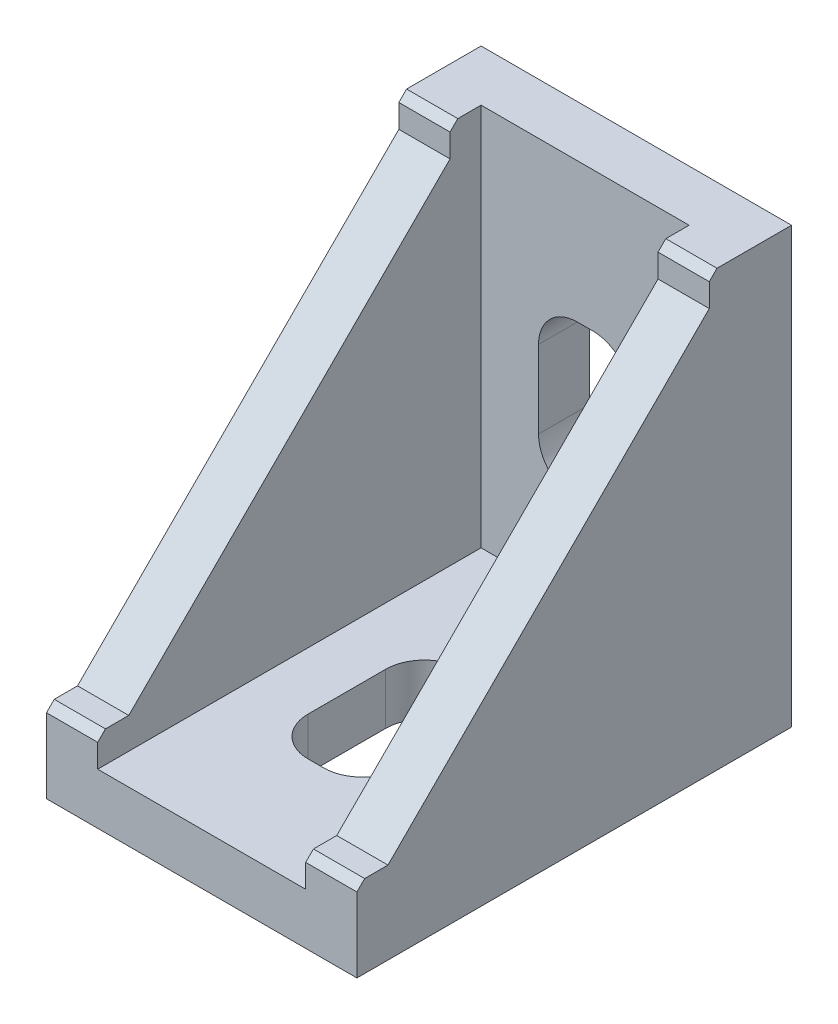
SolidWorks part; units mm, degrees
ref_plane "Front Plane" through (0, 0, 0) normal (0, 0, 1) x (1, 0, 0)
ref_plane "Top Plane" through (0, 0, 0) normal (0, 1, 0) x (1, 0, 0)
ref_plane "Right Plane" through (0, 0, 0) normal (1, 0, 0) x (0, 0, -1)
sketch "Sketch1" plane through (0, 0, 0) normal (0, 0, 1) x (1, 0, 0)
  line L0 (10, 28) -> (10, 0) construction
  line L1 (0, 0) -> (20, 0)
  line L2 (0, 0) -> (0, 28)
  line L3 (0, 28) -> (20, 28)
  line L4 (20, 0) -> (20, 28)
  line L5 (0, 14) -> (20, 14) construction
  line L7 (10.5, 9) -> (9.5, 9)
  line L8 (13, 11.5) -> (13, 16.5)
  line L9 (10.5, 19) -> (9.5, 19)
  line L10 (7, 11.5) -> (7, 16.5)
  line L11 (13, 9) -> (7, 19) construction
  line L12 (13, 19) -> (7, 9) construction
  arc A0 (10.5, 9) -> (13, 11.5) centre (10.5, 11.5) ccw
  arc A1 (13, 16.5) -> (10.5, 19) centre (10.5, 16.5) ccw
  arc A2 (9.5, 9) -> (7, 11.5) centre (9.5, 11.5) cw
  arc A3 (9.5, 19) -> (7, 16.5) centre (9.5, 16.5) ccw
  point P9 (10, 14)
  dimension "D5" = 2.5
  dimension "D1" = 20
  dimension "D2" = 28
  dimension "D3" = 6
  dimension "D4" = 10
extrude "Boss-Extrude1" add sketch "Sketch1" against normal blind 3.3
sketch "Sketch2" plane through (0, 0, 0) normal (0, 1, 0) x (1, 0, 0)
  line L0 (10, -24.7) -> (10, 0) construction
  line L1 (0, 0) -> (20, 0)
  line L2 (0, 0) -> (0, -24.7)
  line L3 (0, -24.7) -> (20, -24.7)
  line L4 (20, 0) -> (20, -24.7)
  line L5 (10, -12.35) -> (0, -12.35) construction
  line L7 (10.5, -17.35) -> (9.5, -17.35)
  line L8 (13, -14.85) -> (13, -9.85)
  line L9 (10.5, -7.35) -> (9.5, -7.35)
  line L10 (7, -14.85) -> (7, -9.85)
  line L11 (13, -17.35) -> (7, -7.35) construction
  line L12 (13, -7.35) -> (7, -17.35) construction
  arc A0 (10.5, -17.35) -> (13, -14.85) centre (10.5, -14.85) ccw
  arc A1 (9.5, -17.35) -> (7, -14.85) centre (9.5, -14.85) cw
  arc A2 (13, -9.85) -> (10.5, -7.35) centre (10.5, -9.85) ccw
  arc A3 (9.5, -7.35) -> (7, -9.85) centre (9.5, -9.85) ccw
  dimension "D5" = 2.5
  dimension "D1" = 24.7
  dimension "D2" = 20
  dimension "D3" = 6
  dimension "D4" = 10
extrude "Boss-Extrude2" add sketch "Sketch2" along normal blind 3.3
sketch "Sketch3" plane through (0, 0, 0) normal (1, 0, 0) x (0, 0, -1)
  line L0 (0, 28) -> (-2, 28)
  line L1 (-2, 28) -> (-2, 26)
  line L2 (-24.7, 3.3) -> (-24.7, 5.3)
  line L3 (-24.7, 5.3) -> (-22.7, 5.3)
  line L4 (-22.7, 5.3) -> (-2, 26)
  line L5 (0, 28) -> (0, 3.3)
  line L6 (0, 3.3) -> (-24.7, 3.3)
  dimension "D1" = 2
  dimension "D2" = 2
  dimension "D3" = 2
  dimension "D4" = 2
extrude "Boss-Extrude3" add sketch "Sketch3" along normal blind 3.3
sketch "Sketch4" plane through (20, 0, 0) normal (1, 0, 0) x (0, 0, -1)
  line L0 (0, 28) -> (-2, 28)
  line L1 (-2, 28) -> (-2, 26)
  line L2 (-2, 26) -> (-22.7, 5.3)
  line L3 (-22.7, 5.3) -> (-24.7, 5.3)
  line L4 (-24.7, 5.3) -> (-24.7, 3.3)
  line L5 (-24.7, 3.3) -> (0, 3.3)
  line L6 (0, 3.3) -> (0, 28)
extrude "Boss-Extrude4" add sketch "Sketch4" against normal blind 3.3
chamfer "Chamfer1" distance 0.5 angle 45 4 edges at (18.35, 5.3, 24.7) (1.65, 5.3, 24.7) (18.35, 28, 2) (1.65, 28, 2)
sketch "Sketch5" plane through (0, 0, -3.3) normal (0, 0, -1) x (-1, 0, 0)
  line L0 (-10, 0) -> (-10, 28) construction
  line L1 (0, 0) -> (-20, 0) construction
  line L2 (-20, 28) -> (0, 28) construction
  line L3 (-10, 14) -> (0, 14) construction
  line L4 (-12.15, 22) -> (-7.85, 22)
  line L5 (-12.15, 22) -> (-12.15, 25)
  line L6 (-12.15, 25) -> (-7.85, 25)
  line L7 (-7.85, 22) -> (-7.85, 25)
  line L8 (-12.15, 22) -> (-7.85, 25) construction
  line L9 (-12.15, 25) -> (-7.85, 22) construction
  line L10 (0, 28) -> (0, 0) construction
  line L11 (-12.15, 3) -> (-7.85, 3)
  line L12 (-7.85, 6) -> (-7.85, 3)
  line L13 (-12.15, 6) -> (-7.85, 6)
  line L14 (-12.15, 6) -> (-12.15, 3)
  point P6 (-10, 23.5)
  dimension "D1" = 3
  dimension "D2" = 4.3
  dimension "D3" = 4.5
extrude "Boss-Extrude5" add sketch "Sketch5" along normal blind 1
sketch "Sketch6" plane through (0, 0, 0) normal (0, -1, 0) x (1, 0, 0)
  line L0 (10, -3.3) -> (10, 24.7) construction
  line L1 (0, -3.3) -> (20, -3.3) construction
  line L2 (0, 24.7) -> (20, 24.7) construction
  line L3 (10, 10.7) -> (20, 10.7) construction
  line L4 (20, -3.3) -> (20, 24.7) construction
  line L5 (12.15, -0.3) -> (7.85, -0.3)
  line L6 (12.15, 18.7) -> (7.85, 18.7)
  line L7 (12.15, 18.7) -> (12.15, 21.7)
  line L8 (12.15, 21.7) -> (7.85, 21.7)
  line L9 (7.85, 18.7) -> (7.85, 21.7)
  line L10 (12.15, 18.7) -> (7.85, 21.7) construction
  line L11 (12.15, 21.7) -> (7.85, 18.7) construction
  line L12 (7.85, 2.7) -> (7.85, -0.3)
  line L13 (12.15, 2.7) -> (7.85, 2.7)
  line L14 (12.15, 2.7) -> (12.15, -0.3)
  point P10 (10, 20.2)
  dimension "D1" = 4.3
  dimension "D2" = 3
  dimension "D3" = 4.5
extrude "Boss-Extrude6" add sketch "Sketch6" along normal blind 1
